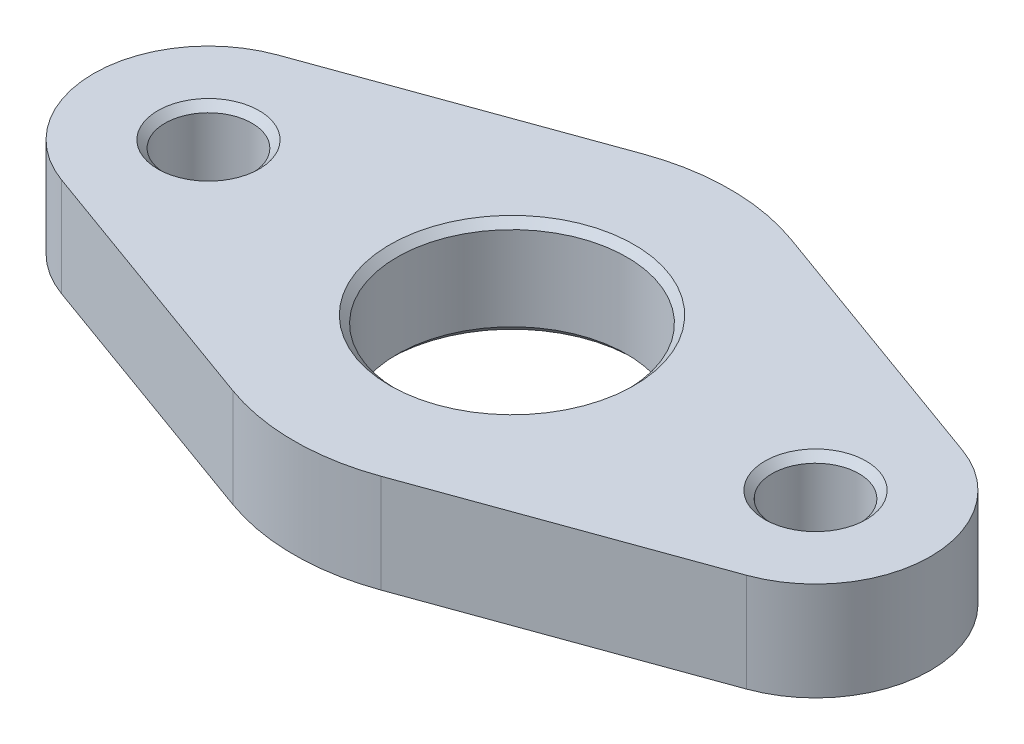
SolidWorks part; units mm, degrees
ref_plane "Front Plane" through (0, 0, 0) normal (0, 0, 1) x (1, 0, 0)
ref_plane "Top Plane" through (0, 0, 0) normal (0, 1, 0) x (1, 0, 0)
ref_plane "Right Plane" through (0, 0, 0) normal (1, 0, 0) x (0, 0, -1)
sketch "Sketch1" plane through (0, 0, 0) normal (0, 1, 0) x (1, 0, 0)
  line L0 (-37.8654, 11.9444) -> (-8.189, 22.6661)
  line L1 (-55, 0) -> (55, 0) construction
  line L2 (-37.8654, -11.9444) -> (-8.189, -22.6661)
  line L3 (0, -55) -> (0, 55) construction
  line L4 (37.8654, 11.9444) -> (8.189, 22.6661)
  line L5 (37.8654, -11.9444) -> (8.189, -22.6661)
  arc A0 (-8.189, -22.6661) -> (8.189, -22.6661) centre (0, 0) ccw
  arc A1 (-37.8654, 11.9444) -> (-37.8654, -11.9444) centre (-33.55, 0) ccw
  arc A2 (37.8654, 11.9444) -> (37.8654, -11.9444) centre (33.55, 0) cw
  arc A3 (8.189, 22.6661) -> (-8.189, 22.6661) centre (0, 0) ccw
  circle A4 centre (-33.55, 0) radius 4.8
  circle A5 centre (33.55, 0) radius 4.8
  circle A6 centre (0, 0) radius 12.7
  dimension "D1" = 48.2
  dimension "D2" = 25.4
  dimension "D4" = 9.6
  dimension "D5" = 25.4
  dimension "D3" = 33.55
extrude "Boss-Extrude1" add sketch "Sketch1" along normal mid plane 10.9
chamfer "Chamfer1" distance 0.8 angle 45 6 edges at (-33.55, -5.45, 4.8) (-33.55, 5.45, 4.8) (33.55, -5.45, 4.8) (33.55, 5.45, 4.8) (0, -5.45, 12.7) (0, 5.45, 12.7)
